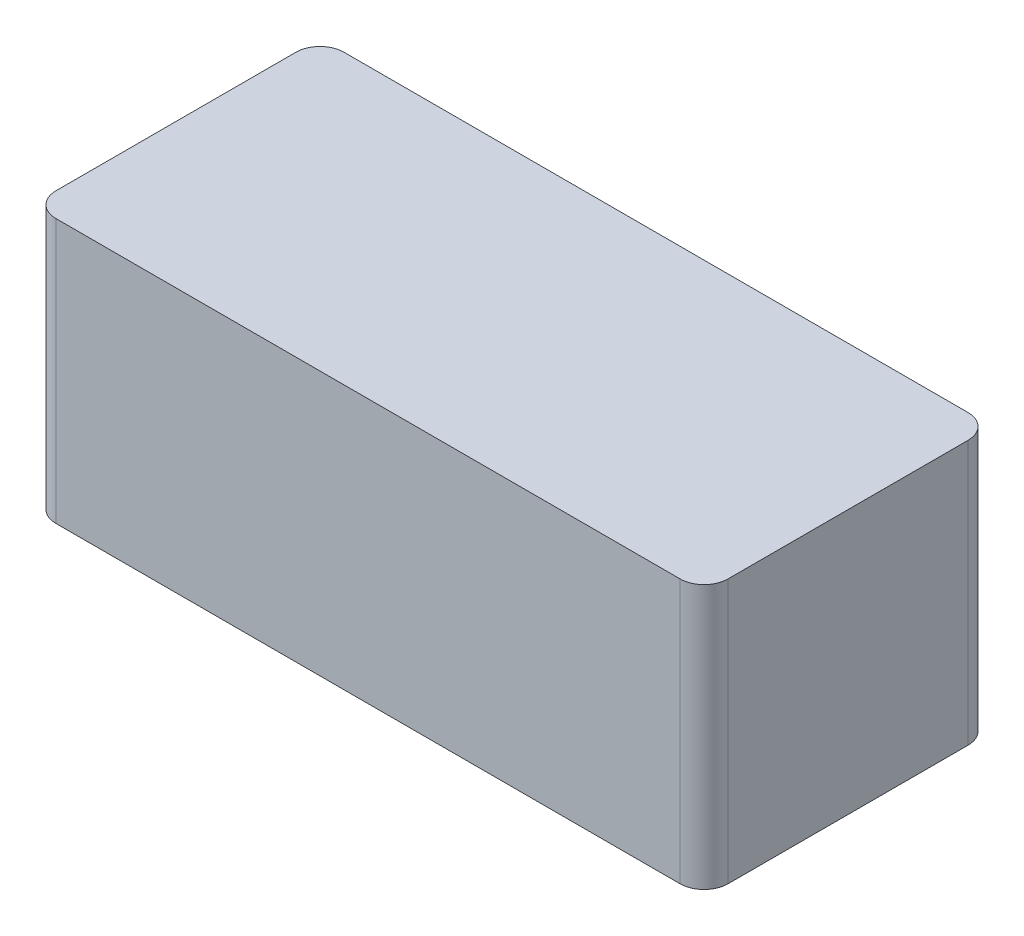
SolidWorks part; units mm, degrees
ref_plane "Front Plane" through (0, 0, 0) normal (0, 0, 1) x (1, 0, 0)
ref_plane "Top Plane" through (0, 0, 0) normal (0, 1, 0) x (1, 0, 0)
ref_plane "Right Plane" through (0, 0, 0) normal (1, 0, 0) x (0, 0, -1)
sketch "Sketch1" plane through (0, 0, 0) normal (0, 1, 0) x (1, 0, 0)
  line L1 (-70, -30) -> (70, -30)
  line L2 (-70, -30) -> (-70, 30)
  line L3 (-70, 30) -> (70, 30)
  line L4 (70, -30) -> (70, 30)
  line L5 (-70, -30) -> (70, 30) construction
  line L6 (-70, 30) -> (70, -30) construction
  point P0 (0, 0)
  dimension "D1" = 140
  dimension "D2" = 60
extrude "Boss-Extrude1" add sketch "Sketch1" along normal blind 55
fillet "Fillet1" radius 5 4 edges at (70, 27.5, 30) (70, 27.5, -30) (-70, 27.5, 30) (-70, 27.5, -30)
